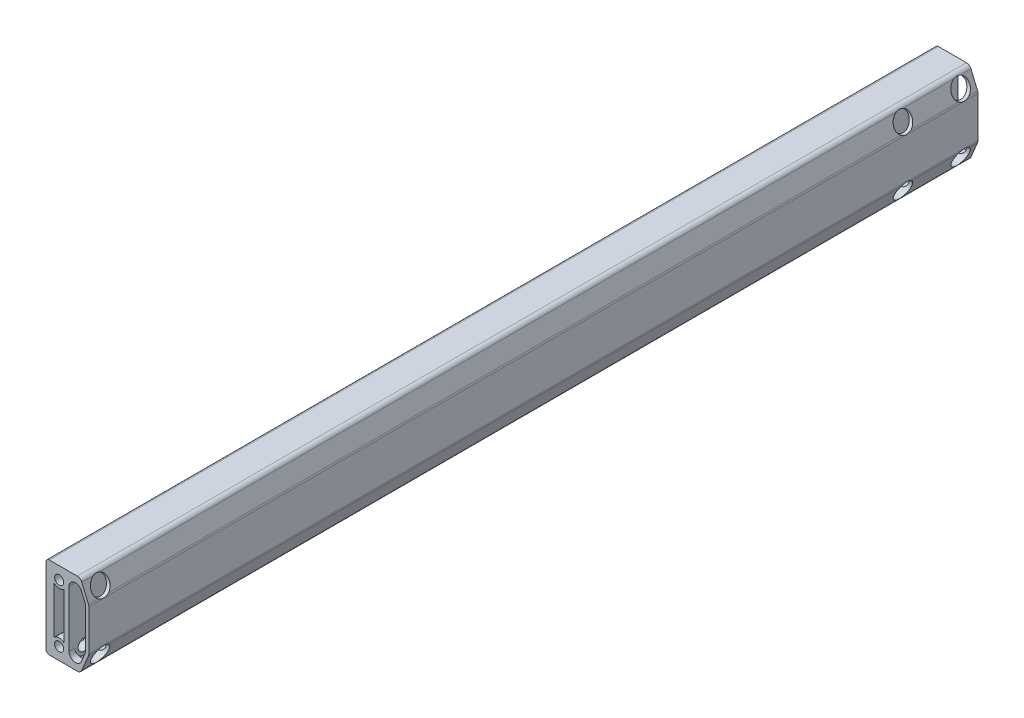
SolidWorks part; units mm, degrees
ref_plane "前视基准面" through (0, 0, 0) normal (0, 0, 1) x (1, 0, 0)
ref_plane "上视基准面" through (0, 0, 0) normal (0, 1, 0) x (1, 0, 0)
ref_plane "右视基准面" through (0, 0, 0) normal (1, 0, 0) x (0, 0, -1)
sketch "草图1" plane through (0, 0, 0) normal (0, 0, 1) x (1, 0, 0)
  line L127 (1267.4411, 1153.2807) -> (1313.3964, 1153.2807) construction
  line L129 (1284.9549, 1167.4266) -> (1284.9549, 1139.1348)
  line L130 (1279.9549, 1143.2807) -> (1279.9549, 1130.2807)
  line L134 (1279.9549, 1176.2807) -> (1279.9549, 1163.2807)
  line L135 (1298.9549, 1128.2807) -> (1281.9549, 1128.2807)
  line L136 (1281.9549, 1178.2807) -> (1298.9549, 1178.2807)
  line L137 (1290.9549, 1167.4266) -> (1290.9549, 1139.1348)
  line L138 (1293.9549, 1170.3807) -> (1293.9549, 1136.1807)
  line L139 (1305.9549, 1140.8807) -> (1305.9549, 1165.6807)
  line L140 (1303.9549, 1140.8807) -> (1303.9549, 1165.6807)
  line L141 (1305.7241, 1166.8346) -> (1301.7241, 1176.4346)
  line L142 (1303.8779, 1166.0653) -> (1301.4549, 1171.8807)
  line L143 (1305.7241, 1139.7269) -> (1301.7241, 1130.1269)
  line L144 (1303.8779, 1140.4961) -> (1301.4549, 1134.6807)
  line L145 (1279.9549, 1163.2807) -> (1279.9549, 1143.2807)
  arc A25 (1301.7241, 1176.4346) -> (1298.9549, 1178.2807) centre (1298.9549, 1175.2807) ccw
  arc A26 (1281.9549, 1178.2807) -> (1279.9549, 1176.2807) centre (1281.9549, 1176.2807) ccw
  arc A27 (1279.9549, 1130.2807) -> (1281.9549, 1128.2807) centre (1281.9549, 1130.2807) ccw
  arc A28 (1305.9549, 1165.6807) -> (1305.7241, 1166.8346) centre (1302.9549, 1165.6807) ccw
  arc A29 (1303.9549, 1165.6807) -> (1303.8779, 1166.0653) centre (1302.9549, 1165.6807) ccw
  arc A30 (1305.7241, 1139.7269) -> (1305.9549, 1140.8807) centre (1302.9549, 1140.8807) ccw
  arc A31 (1303.8779, 1140.4961) -> (1303.9549, 1140.8807) centre (1302.9549, 1140.8807) ccw
  arc A32 (1298.9549, 1128.2807) -> (1301.7241, 1130.1269) centre (1298.9549, 1131.2807) ccw
  arc A33 (1301.4549, 1171.8807) -> (1293.9549, 1170.3807) centre (1297.8549, 1170.3807) ccw
  arc A34 (1293.9549, 1136.1807) -> (1301.4549, 1134.6807) centre (1297.8549, 1136.1807) ccw
  circle A35 centre (1287.9549, 1135.7807) radius 2.75
  circle A36 centre (1287.9549, 1170.7807) radius 2.75
  arc A37 (1290.9549, 1139.1348) -> (1284.9549, 1139.1348) centre (1287.9549, 1135.7807) ccw
  arc A38 (1284.9549, 1167.4266) -> (1290.9549, 1167.4266) centre (1287.9549, 1170.7807) ccw
extrude "拉伸1" add sketch "草图1" against normal blind 540
sketch "草图2" plane through (1279.9549, 0, 0) normal (-1, 0, 0) x (0, 0, 1)
  line L0 (-540, 1153.2807) -> (0, 1153.2807) construction
  line L1 (-540, 1176.2807) -> (-540, 1130.2807) construction
  line L2 (0, 1176.2807) -> (0, 1130.2807) construction
  line L3 (-540, 1163.2807) -> (-485, 1163.2807)
  line L5 (-485, 1143.2807) -> (-540, 1143.2807)
  line L6 (-540, 1143.2807) -> (-540, 1163.2807)
  arc A0 (-485, 1143.2807) -> (-485, 1163.2807) centre (-485, 1153.2807) ccw
  dimension "D1" = 55
  dimension "D2" = 10
  dimension "D3" = 20
extrude "拉伸2" cut sketch "草图2" against normal blind 2.5
sketch "草图3" plane through (1305.9549, 0, 0) normal (1, 0, 0) x (0, 0, -1)
  line L0 (540, 1153.2807) -> (0, 1153.2807) construction
  line L1 (540, 1140.8807) -> (540, 1165.6807) construction
  line L2 (0, 1140.8807) -> (0, 1165.6807) construction
  line L3 (540, 1166.8346) -> (540, 1176.4346) construction
  circle A0 centre (531.5, 1171.2807) radius 3.5
  circle A1 centre (496.5, 1171.2807) radius 3.5
  circle A2 centre (531.5, 1135.2807) radius 3.5
  circle A3 centre (496.5, 1135.2807) radius 3.5
  circle A4 centre (9, 1171.2807) radius 3.5
  circle A5 centre (9, 1135.2807) radius 3.5
  dimension "D1" = 7
  dimension "D2" = 7
  dimension "D3" = 7
  dimension "D4" = 7
  dimension "D5" = 7
  dimension "D6" = 7
  dimension "D8" = 18
  dimension "D9" = 9
  dimension "D16" = 35
  dimension "D17" = 35
  dimension "D7" = 36
  dimension "D10" = 36
  dimension "D11" = 36
  dimension "D12" = 18
  dimension "D13" = 18
  dimension "D14" = 8.5
  dimension "D15" = 8.5
extrude "拉伸3" cut sketch "草图3" against normal through all
sketch "草图4" plane through (1305.9549, 0, 0) normal (1, 0, 0) x (0, 0, -1)
  circle A0 centre (496.5, 1171.2807) radius 5.5
  circle A1 centre (531.5, 1171.2807) radius 5.5
  circle A2 centre (496.5, 1135.2807) radius 5.5
  circle A3 centre (531.5, 1135.2807) radius 5.5
  circle A4 centre (9, 1171.2807) radius 5.5
  circle A5 centre (9, 1135.2807) radius 5.5
  dimension "D1" = 11
  dimension "D2" = 11
  dimension "D3" = 11
  dimension "D4" = 11
  dimension "D5" = 11
  dimension "D6" = 11
extrude "拉伸4" cut sketch "草图4" against normal blind 12
